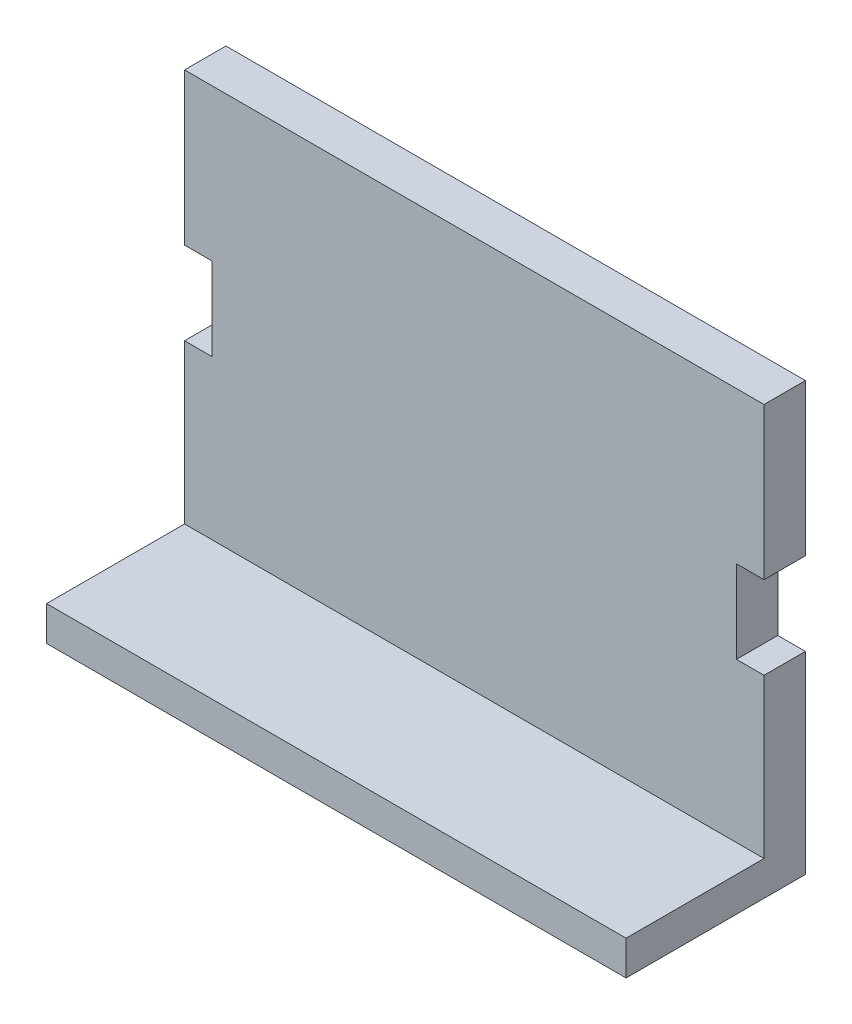
SolidWorks part; units mm, degrees
ref_plane "Front Plane" through (0, 0, 0) normal (0, 0, 1) x (1, 0, 0)
ref_plane "Top Plane" through (0, 0, 0) normal (0, 1, 0) x (1, 0, 0)
ref_plane "Right Plane" through (0, 0, 0) normal (1, 0, 0) x (0, 0, -1)
sketch "Sketch1" plane through (0, 0, 0) normal (0, 0, 1) x (1, 0, 0)
  line L0 (84, 62) -> (84, 40)
  line L1 (0, 0) -> (84, 0)
  line L2 (0, 0) -> (0, 28)
  line L3 (0, 62) -> (84, 62)
  line L4 (84, 0) -> (84, 28)
  line L6 (84, 28) -> (80, 28)
  line L7 (80, 28) -> (80, 40)
  line L8 (80, 40) -> (84, 40)
  line L9 (0, 28) -> (4, 28)
  line L10 (4, 28) -> (4, 40)
  line L11 (4, 40) -> (0, 40)
  line L12 (0, 40) -> (0, 62)
  dimension "D1" = 84
  dimension "D2" = 62
extrude "Boss-Extrude1" add sketch "Sketch1" along normal blind 6
sketch "Sketch2" plane through (0, 0, 6) normal (0, 0, 1) x (1, 0, 0)
  line L0 (0, 0) -> (0, 5)
  line L1 (0, 5) -> (84, 5)
  line L2 (84, 0) -> (84, 28) construction
  line L3 (84, 5) -> (84, 0)
  line L4 (84, 0) -> (0, 0)
extrude "Boss-Extrude2" add sketch "Sketch2" along normal blind 20
